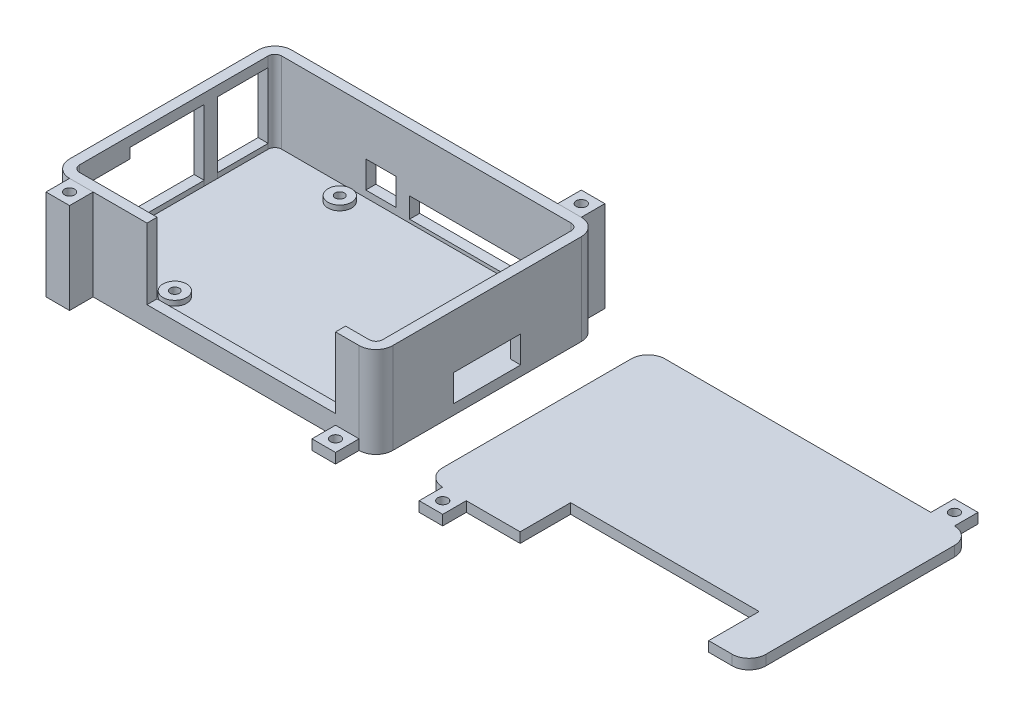
SolidWorks part; units mm, degrees
ref_plane "Alzado" through (0, 0, 0) normal (0, 0, 1) x (1, 0, 0)
ref_plane "Planta" through (0, 0, 0) normal (0, 1, 0) x (1, 0, 0)
ref_plane "Vista lateral" through (0, 0, 0) normal (1, 0, 0) x (0, 0, -1)
sketch "Croquis1" plane through (0, 0, 0) normal (0, 1, 0) x (1, 0, 0)
  line L1 (43, 30) -> (-43, 30)
  line L2 (45, 28) -> (45, -28)
  line L3 (43, -30) -> (-43, -30)
  line L4 (-45, 28) -> (-45, -28)
  line L5 (45, 30) -> (-45, -30) construction
  line L6 (45, -30) -> (-45, 30) construction
  arc A0 (43, 30) -> (45, 28) centre (43, 28) cw
  arc A1 (45, -28) -> (43, -30) centre (43, -28) cw
  arc A2 (-43, -30) -> (-45, -28) centre (-43, -28) cw
  arc A3 (-43, 30) -> (-45, 28) centre (-43, 28) ccw
  point P0 (0, 0)
  dimension "D3" = 2
  dimension "D1" = 60
  dimension "D2" = 90
extrude "Extruir-Lámina1" add sketch "Croquis1" along normal blind 24 thin
sketch "Croquis3" plane through (0, 0, 0) normal (0, -1, 0) x (1, 0, 0)
  line L0 (-43, 33) -> (43, 33) construction
  line L1 (-43, 33) -> (43, 33)
  line L2 (-48, -28) -> (-48, 28) construction
  line L3 (-48, -28) -> (-48, 28)
  line L4 (48, 28) -> (48, -28) construction
  line L5 (43, -33) -> (-43, -33) construction
  line L6 (48, 28) -> (48, -28)
  line L7 (43, -33) -> (-43, -33)
  arc A0 (-43, 33) -> (-48, 28) centre (-43, 28) ccw construction
  arc A1 (-43, 33) -> (-48, 28) centre (-43, 28) ccw
  arc A2 (48, 28) -> (43, 33) centre (43, 28) ccw construction
  arc A3 (43, -33) -> (48, -28) centre (43, -28) ccw construction
  arc A4 (-48, -28) -> (-43, -33) centre (-43, -28) ccw construction
  arc A5 (48, 28) -> (43, 33) centre (43, 28) ccw
  arc A6 (43, -33) -> (48, -28) centre (43, -28) ccw
  arc A7 (-48, -28) -> (-43, -33) centre (-43, -28) ccw
extrude "Saliente-Extruir1" add sketch "Croquis3" along normal blind 3
sketch "Croquis4" plane through (-48, 0, 0) normal (-1, 0, 0) x (0, 0, 1)
  line L0 (28, 24) -> (28, -3) construction
  line L2 (28, 0) -> (28, 18)
  line L3 (28, 18) -> (13, 18)
  line L5 (-28, 24) -> (-28, -3) construction
  line L6 (28, 0) -> (-9, 0)
  line L7 (13, 18) -> (13, 21)
  line L8 (13, 21) -> (-9, 21)
  line L9 (-9, 0) -> (-9, 21)
  line L10 (-13, 0) -> (-28, 0)
  line L11 (-13, 0) -> (-13, 21)
  line L12 (-13, 21) -> (-28, 21)
  line L13 (-28, 0) -> (-28, 21)
  line L14 (28, -3) -> (-28, -3) construction
  point P19 (13, 0)
  point P20 (0, 0)
  point P21 (0, 0)
  point P22 (0, 0)
  point P23 (27.5752, 0)
  dimension "D1" = 41
  dimension "D2" = 18
  dimension "D3" = 3
  dimension "D4" = 15
  dimension "D5" = 4
  dimension "D6" = 21
extrude "Cortar-Extruir1" cut sketch "Croquis4" against normal up to next
sketch "Croquis5" plane through (0, 0, 33) normal (0, 0, 1) x (1, 0, 0)
  line L0 (-43, 24) -> (43, 24) construction
  line L1 (36, 3) -> (-20, 3)
  line L2 (36, 3) -> (36, 24)
  line L3 (36, 24) -> (-20, 24)
  line L4 (-20, 3) -> (-20, 24)
  line L5 (43, 24) -> (43, -3) construction
  dimension "D1" = 7
  dimension "D2" = 56
  dimension "D3" = 21
extrude "Cortar-Extruir2" cut sketch "Croquis5" against normal up to next
sketch "Croquis7" plane through (0, 0, -33) normal (0, 0, -1) x (-1, 0, 0)
  line L1 (-36, 7) -> (5, 7)
  line L2 (-36, 7) -> (-36, 1)
  line L3 (-36, 1) -> (5, 1)
  line L4 (5, 7) -> (5, 1)
  line L6 (-43, 24) -> (-43, -3) construction
  line L7 (9, 10) -> (18, 10)
  line L8 (9, 10) -> (9, 2)
  line L9 (9, 2) -> (18, 2)
  line L10 (18, 10) -> (18, 2)
  dimension "D1" = 1
  dimension "D2" = 6
  dimension "D3" = 41
  dimension "D4" = 2
  dimension "D5" = 8
  dimension "D6" = 9
  dimension "D7" = 4
  dimension "D8" = 7
extrude "Cortar-Extruir3" cut sketch "Croquis7" against normal up to next
sketch "Croquis8" plane through (0, 24, 0) normal (0, 1, 0) x (1, 0, 0)
  line L1 (-43, -33) -> (-36, -33)
  line L2 (-43, -33) -> (-43, -40)
  line L3 (-43, -40) -> (-36, -40)
  line L4 (-36, -33) -> (-36, -40)
  line L5 (43, 33) -> (36, 33)
  line L6 (43, 33) -> (43, 40)
  line L7 (43, 40) -> (36, 40)
  line L8 (36, 33) -> (36, 40)
  dimension "D1" = 7
  dimension "D2" = 7
  dimension "D3" = 7
  dimension "D4" = 7
extrude "Saliente-Extruir5" add sketch "Croquis8" against normal blind 27 separate body
sketch "Croquis10" plane through (0, 24, 0) normal (0, 1, 0) x (1, 0, 0)
  line L0 (-43, -36.5) -> (-36, -36.5) construction
  line L1 (-43, -33) -> (-43, -40) construction
  line L2 (-36, -40) -> (-36, -33) construction
  line L3 (-39.5, -40) -> (-39.5, -33) construction
  line L4 (-43, -40) -> (-36, -40) construction
  line L5 (-36, -33) -> (-43, -33) construction
  line L6 (36, 36.5) -> (43, 36.5) construction
  line L7 (36, 40) -> (36, 33) construction
  line L8 (43, 33) -> (43, 40) construction
  line L9 (39.5, 33) -> (39.5, 40) construction
  line L10 (36, 33) -> (43, 33) construction
  line L11 (43, 40) -> (36, 40) construction
  circle A0 centre (-39.5, -36.5) radius 1.5
  circle A1 centre (39.5, 36.5) radius 1.5
  dimension "D1" = 3
  dimension "D2" = 3
extrude "Cortar-Extruir4" cut sketch "Croquis10" against normal blind 20
sketch "Croquis11" plane through (0, 0, 0) normal (0, 1, 0) x (1, 0, 0)
  line L0 (-20, -33) -> (36, -33) construction
  line L1 (43, 33) -> (-43, 33) construction
  line L3 (146.8404, 36.5) -> (153.8404, 36.5) construction
  line L4 (150.3404, 40) -> (150.3404, 36.5) construction
  line L6 (67.8404, -36.5) -> (74.8404, -36.5) construction
  line L7 (71.3404, -40) -> (71.3404, -36.5) construction
  line L24 (67.8404, -33) -> (67.8404, -40)
  line L25 (67.8404, -40) -> (74.8404, -40)
  line L26 (74.8404, -40) -> (74.8404, -33)
  line L27 (150.8404, -33) -> (153.8404, -33)
  line L28 (74.8404, -33) -> (150.8404, -33)
  line L29 (158.8404, -28) -> (158.8404, 28)
  line L30 (146.8404, 40) -> (146.8404, 33)
  line L31 (153.8404, 40) -> (146.8404, 40)
  line L32 (153.8404, 33) -> (153.8404, 40)
  line L33 (146.8404, 33) -> (67.8404, 33)
  line L34 (62.8404, 28) -> (62.8404, -28)
  circle A0 centre (71.3404, -36.5) radius 1.5
  arc A10 (62.8404, -28) -> (67.8404, -33) centre (67.8404, -28) ccw
  arc A11 (153.8404, -33) -> (158.8404, -28) centre (153.8404, -28) ccw
  arc A12 (158.8404, 28) -> (153.8404, 33) centre (153.8404, 28) ccw
  circle A13 centre (150.3404, 36.5) radius 1.5
  arc A14 (67.8404, 33) -> (62.8404, 28) centre (67.8404, 28) ccw
  dimension "D1" = 3
  dimension "D2" = 5
  dimension "D3" = 62.8404
  dimension "D4" = 71.3404
  dimension "D5" = 146.8404
  dimension "D6" = 150.8404
extrude "Saliente-Extruir6" add sketch "Croquis11" against normal blind 3 separate body
sketch "Croquis12" plane through (-48, 0, 0) normal (-1, 0, 0) x (0, 0, 1)
  line L0 (-28, 24) -> (-28, 0) construction
  line L1 (-28, 1.5) -> (-13, 1.5)
  line L2 (-28, 1.5) -> (-28, 0)
  line L3 (-28, 0) -> (-13, 0)
  line L4 (-13, 1.5) -> (-13, 0)
  line L5 (-28, 0) -> (-13, 0) construction
  line L6 (28, 0) -> (-28, 0) construction
  line L7 (-9, 21) -> (-9, 0) construction
  line L8 (-9, 1.5) -> (28, 1.5)
  line L9 (-9, 1.5) -> (-9, 0)
  line L10 (-9, 0) -> (28, 0)
  line L11 (28, 1.5) -> (28, 0)
  line L12 (-13, 0) -> (-13, 21) construction
  dimension "D1" = 1.5
extrude "Saliente-Extruir7" add sketch "Croquis12" against normal blind 3 separate body
sketch "Croquis13" plane through (0, 0, 0) normal (0, 1, 0) x (1, 0, 0)
  line L0 (43, 30) -> (-43, 30) construction
  line L1 (45, -28) -> (45, 28) construction
  circle A0 centre (37.03, -23.77) radius 1.35
  circle A1 centre (-20.97, -23.77) radius 1.35
  circle A2 centre (37.03, 25.23) radius 1.35
  circle A3 centre (-20.97, 25.23) radius 1.35
  circle A4 centre (-20.97, 25.23) radius 3.5
  circle A5 centre (37.03, -23.77) radius 3.5
  circle A6 centre (-20.97, -23.77) radius 3.5
  circle A7 centre (37.03, 25.23) radius 3.5
  dimension "D1" = 2.7
  dimension "D2" = 4.77
  dimension "D6" = 7
  dimension "D7" = 7
  dimension "D8" = 7
  dimension "D9" = 7
  dimension "D3" = 7.97
  dimension "D4" = 58
  dimension "D5" = 49
extrude "Saliente-Extruir8" add sketch "Croquis13" along normal blind 1.5
sketch "Croquis14" plane through (0, 0, 0) normal (0, 1, 0) x (1, 0, 0)
  circle A0 centre (37.03, -23.77) radius 1.35 construction
  circle A1 centre (-20.97, -23.77) radius 1.35 construction
  circle A2 centre (37.03, 25.23) radius 1.35 construction
  circle A3 centre (-20.97, 25.23) radius 1.35 construction
  circle A4 centre (37.03, -23.77) radius 1.35
  circle A5 centre (-20.97, -23.77) radius 1.35
  circle A6 centre (37.03, 25.23) radius 1.35
  circle A7 centre (-20.97, 25.23) radius 1.35
extrude "Cortar-Extruir5" cut sketch "Croquis14" against normal through all and the other way blind 2
sketch "Croquis15" plane through (0, -3, 0) normal (0, -1, 0) x (-1, 0, 0)
  line L1 (-90.8404, -33) -> (-146.8404, -33)
  line L2 (-90.8404, -33) -> (-90.8404, -18)
  line L3 (-90.8404, -18) -> (-146.8404, -18)
  line L4 (-146.8404, -33) -> (-146.8404, -18)
  line L9 (-74.8404, -33) -> (-153.8404, -33) construction
  dimension "D1" = 56
  dimension "D2" = 15
  dimension "D3" = 7
extrude "Cortar-Extruir6" cut sketch "Croquis15" against normal through all
sketch "Croquis16" plane through (0, 0, 0) normal (0, 1, 0) x (1, 0, 0)
  line L0 (-39.5, 40) -> (-39.5, 33) construction
  line L1 (-43, 33) -> (-36, 33)
  line L2 (-43, 33) -> (-43, 40)
  line L3 (-43, 40) -> (-36, 40)
  line L4 (-36, 33) -> (-36, 40)
  line L5 (-43, 36.5) -> (-36, 36.5) construction
  line L6 (39.5, -40) -> (39.5, -33) construction
  line L7 (43, -33) -> (36, -33)
  line L8 (43, -33) -> (43, -40)
  line L9 (43, -40) -> (36, -40)
  line L10 (36, -33) -> (36, -40)
  line L11 (36, -36.5) -> (43, -36.5) construction
  circle A0 centre (-39.5, 36.5) radius 1.5
  circle A1 centre (39.5, -36.5) radius 1.5
  point P22 (39.5, -36.5)
  dimension "D3" = 3
  dimension "D6" = 3
  dimension "D1" = 7
  dimension "D2" = 7
  dimension "D4" = 7
  dimension "D5" = 7
extrude "Saliente-Extruir9" add sketch "Croquis16" against normal blind 3
sketch "Croquis17" plane through (48, 0, 0) normal (1, 0, 0) x (0, 0, -1)
  line L0 (-28, 0) -> (28, 0) construction
  line L1 (-10, 8) -> (10, 8)
  line L2 (-10, 8) -> (-10, 0)
  line L3 (-10, 0) -> (10, 0)
  line L4 (10, 8) -> (10, 0)
  point P6 (0, 0)
  dimension "D1" = 8
  dimension "D2" = 20
extrude "Cortar-Extruir7" cut sketch "Croquis17" against normal up to next (3 mm away)
